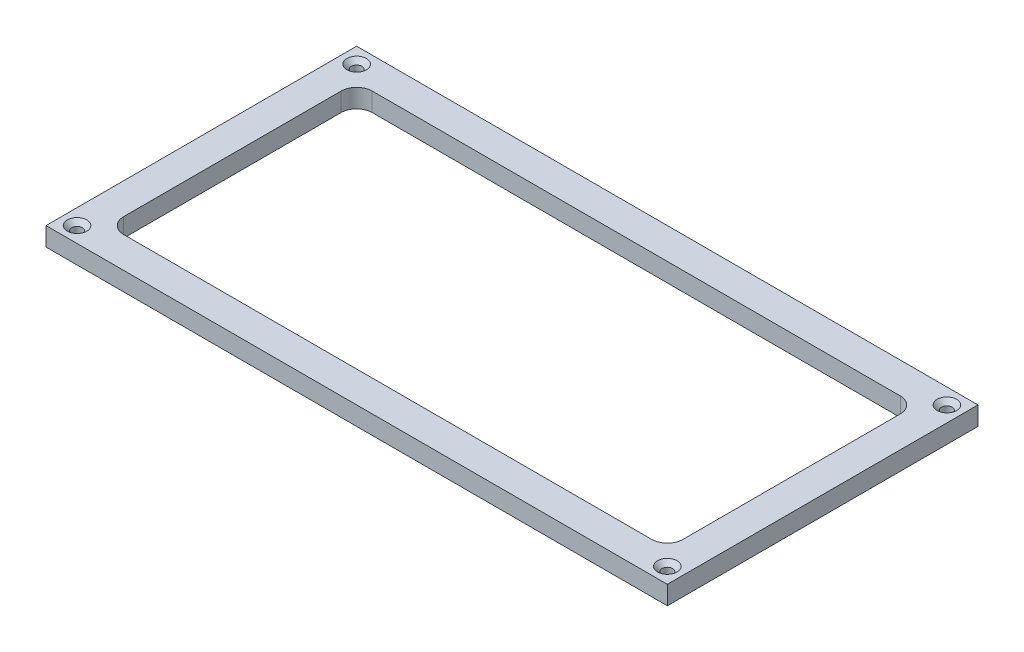
SolidWorks part; units mm, degrees
material "Pine"
ref_plane "Front Plane" through (0, 0, 0) normal (0, 0, 1) x (1, 0, 0)
ref_plane "Top Plane" through (0, 0, 0) normal (0, 1, 0) x (1, 0, 0)
ref_plane "Right Plane" through (0, 0, 0) normal (1, 0, 0) x (0, 0, -1)
sketch "Sketch1" plane through (0, 0, 0) normal (0, 1, 0) x (1, 0, 0)
  line L1 (0, 0) -> (200, 0)
  line L2 (0, 0) -> (0, 100)
  line L3 (0, 100) -> (200, 100)
  line L4 (200, 0) -> (200, 100)
  dimension "D1" = 200
  dimension "D2" = 100
extrude "Boss-Extrude1" add sketch "Sketch1" along normal blind 6
sketch "Sketch2" plane through (0, 6, 0) normal (0, 1, 0) x (1, 0, 0)
  line L0 (0, 100) -> (0, 0) construction
  line L1 (10, 90) -> (190, 90)
  line L2 (10, 90) -> (10, 10)
  line L3 (10, 10) -> (190, 10)
  line L4 (190, 90) -> (190, 10)
  line L5 (200, 0) -> (200, 100) construction
  line L6 (0, 0) -> (200, 0) construction
  line L7 (200, 100) -> (0, 100) construction
  point P6 (200, 50)
  dimension "D1" = 10
  dimension "D2" = 10
  dimension "D3" = 10
  dimension "D4" = 10
extrude "Cut-Extrude1" cut sketch "Sketch2" against normal through all
fillet "Fillet1" radius 5 4 edges at (10, 3, -10) (190, 3, -10) (190, 3, -90) (10, 3, -90)
hole_wizard "CSK for M3 Countersunk Flat Head Screw1" positions "Sketch4" profile "Sketch3" countersink size "M3" standard "DIN" end condition through all
sketch "Sketch4" plane through (0, 6, 0) normal (0, 1, 0) x (1, 0, 0)
  line L0 (0, 100) -> (0, 0) construction
  line L1 (0, 0) -> (200, 0) construction
  line L2 (200, 100) -> (0, 100) construction
  line L3 (200, 0) -> (200, 100) construction
  point P0 (5, 5)
  point P2 (5, 95)
  point P4 (195, 95)
  point P6 (195, 5)
  dimension "D1" = 5
  dimension "D2" = 5
  dimension "D3" = 5
  dimension "D4" = 5
sketch "Sketch3" plane through (5, 6, -5) normal (1, 0, 0) x (0, 0, 1)
  line L0 (0, 0) -> (0, 6)
  line L1 (0, 6) -> (1.7, 6)
  line L2 (1.7, 6) -> (1.7, 1.45)
  line L3 (1.7, 1.45) -> (3.15, 0)
  line L5 (3.15, 0) -> (0, 0)
  line L6 (-1.7, 1.45) -> (-3.15, 0) construction
  line L11 (0, -6.35) -> (0, 107.95) construction
  dimension "Thru Hole Dia." = 3.4
  dimension "Thru Hole Depth" = 6
  dimension "Near C'Sink Dia." = 6.3
  dimension "Near C'Sink Angle" = 90
equation "\"BoardThickness\"= 6"
equation "\"D1@Boss-Extrude1\"=\"BoardThickness\""
equation "\"D2@Sketch2\"=\"D1@Sketch2\""
equation "\"D3@Sketch2\"=\"D1@Sketch2\""
equation "\"D4@Sketch2\"=\"D1@Sketch2\""
